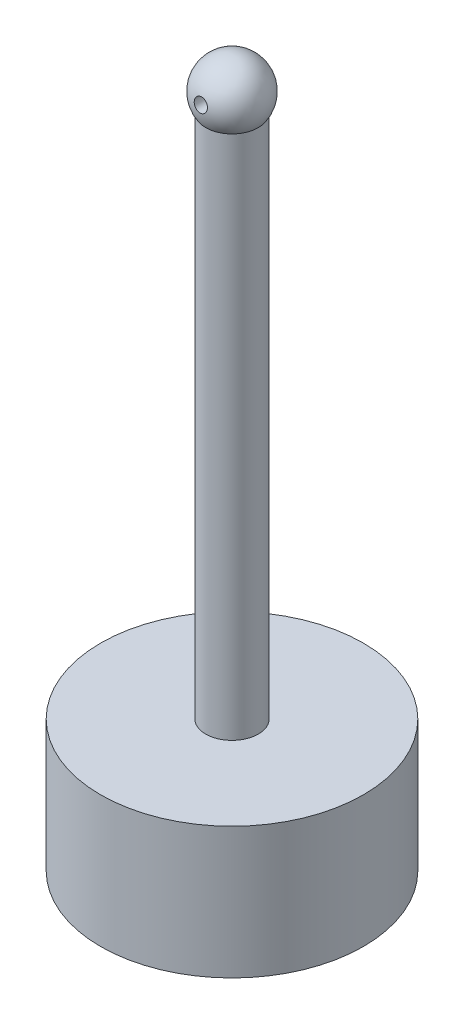
SolidWorks part; units mm, degrees
ref_plane "Front Plane" through (0, 0, 0) normal (0, 0, 1) x (1, 0, 0)
ref_plane "Top Plane" through (0, 0, 0) normal (0, 1, 0) x (1, 0, 0)
ref_plane "Right Plane" through (0, 0, 0) normal (1, 0, 0) x (0, 0, -1)
sketch "Sketch1" plane through (0, 0, 0) normal (0, 1, 0) x (1, 0, 0)
  circle A0 centre (0, 0) radius 500
  dimension "D1" = 1000
extrude "Boss-Extrude1" add sketch "Sketch1" along normal blind 500
sketch "Sketch2" plane through (0, 500, 0) normal (0, 1, 0) x (1, 0, 0)
  circle A0 centre (0, 0) radius 100
  dimension "D1" = 200
extrude "Boss-Extrude2" add sketch "Sketch2" along normal blind 2000
sketch "Sketch3" plane through (0, 2500, 0) normal (0, 1, 0) x (1, 0, 0)
ref_plane "Plane1" through (0, 0, 0) normal (0, 0, 1) x (1, 0, 0)
sketch "Sketch4" plane through (0, 0, 0) normal (0, 0, 1) x (1, 0, 0)
  line L1 (0, 2690.2011) -> (0, 2446.1413)
  circle A0 centre (0, 2568.1712) radius 122.0299
revolve "Revolve3" add sketch "Sketch4" angle 360 about L1
sketch "Sketch5" plane through (0, 0, 0) normal (0, 0, 1) x (1, 0, 0)
  circle A0 centre (0, 2582.5244) radius 25
  dimension "D1" = 50
extrude "Cut-Extrude1" cut sketch "Sketch5" against normal blind 147 and the other way blind 164
